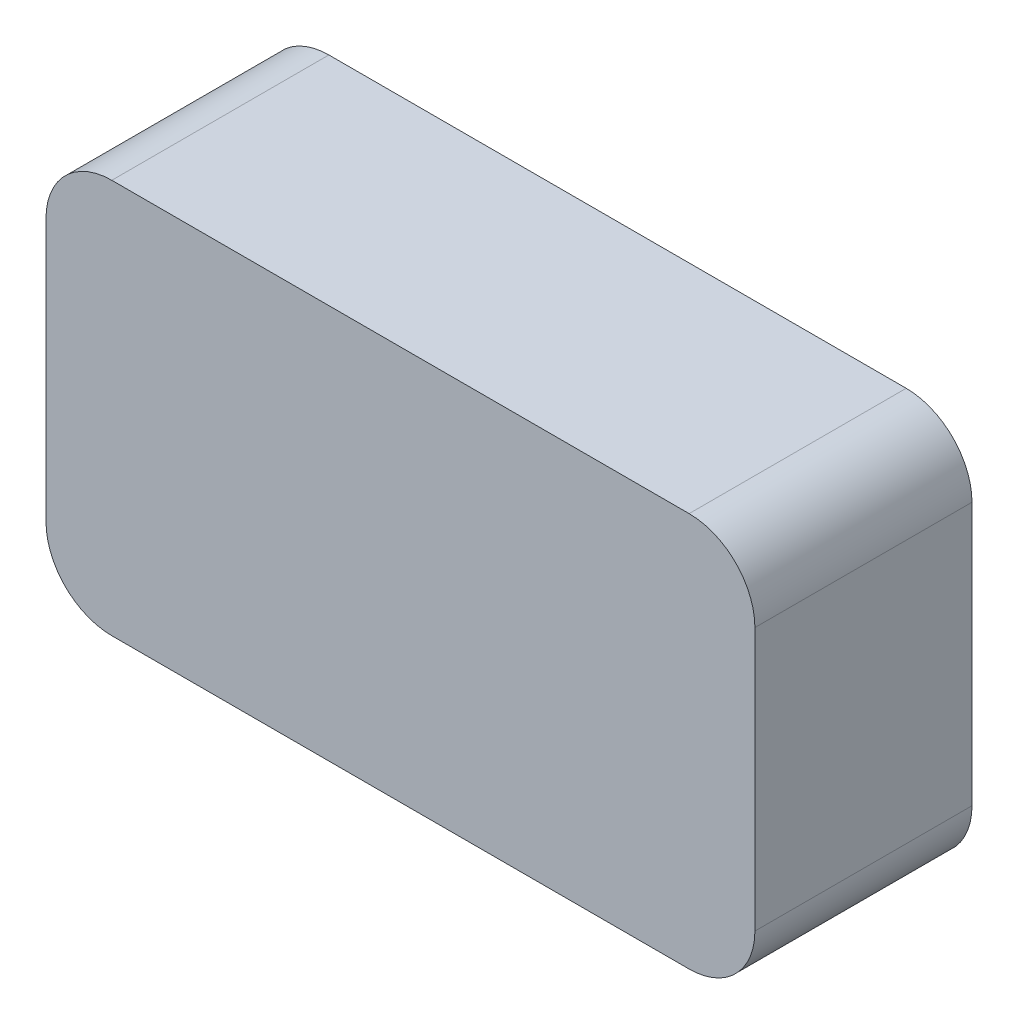
SolidWorks part; units mm, degrees
material "ABS"
ref_plane "前视基准面" through (0, 0, 0) normal (0, 0, 1) x (1, 0, 0)
ref_plane "上视基准面" through (0, 0, 0) normal (0, 1, 0) x (1, 0, 0)
ref_plane "右视基准面" through (0, 0, 0) normal (1, 0, 0) x (0, 0, -1)
sketch "草图1" plane through (0, 0, 0) normal (0, 0, 1) x (1, 0, 0)
  line L1 (53.8823, -29.9787) -> (-53.8823, -29.9787)
  line L2 (53.8823, -29.9787) -> (53.8823, 29.9787)
  line L3 (53.8823, 29.9787) -> (-53.8823, 29.9787)
  line L4 (-53.8823, -29.9787) -> (-53.8823, 29.9787)
  line L5 (53.8823, -29.9787) -> (-53.8823, 29.9787) construction
  line L6 (53.8823, 29.9787) -> (-53.8823, -29.9787) construction
  point P0 (0, 0)
extrude "凸台-拉伸1" add sketch "草图1" along normal blind 33
fillet "圆角1" radius 10 1 edges at (53.8823, 29.9787, 16.5)
fillet "圆角2" radius 10 1 edges at (53.8823, -29.9787, 16.5)
fillet "圆角4" radius 10 1 edges at (-53.8823, 29.9787, 16.5)
fillet "圆角5" radius 10 1 edges at (-53.8823, -29.9787, 16.5)
sketch "草图2" plane through (0, 0, 0) normal (0, 0, -1) x (-1, 0, 0)
  circle A0 centre (-36.1089, 0) radius 2.5469
extrude "凸台-拉伸2" add sketch "草图2" along normal blind 3
